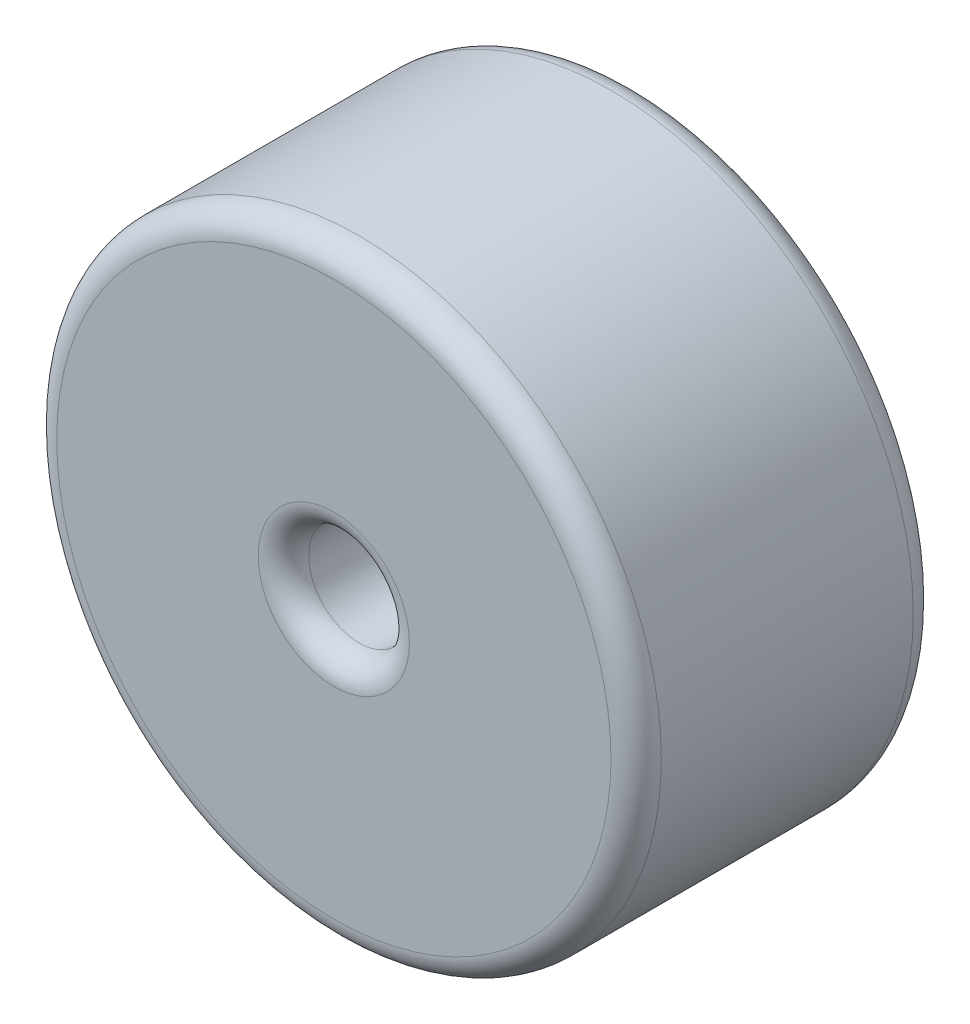
SolidWorks part; units mm, degrees
ref_plane "前视基准面" through (0, 0, 0) normal (0, 0, 1) x (1, 0, 0)
ref_plane "上视基准面" through (0, 0, 0) normal (0, 1, 0) x (1, 0, 0)
ref_plane "右视基准面" through (0, 0, 0) normal (1, 0, 0) x (0, 0, -1)
sketch "草图1" plane through (0, 0, 0) normal (0, 0, 1) x (1, 0, 0)
  circle A0 centre (0, 0) radius 12
  dimension "D1" = 24
extrude "凸台-拉伸1" add sketch "草图1" along normal blind 12
fillet "圆角1" radius 1 2 edges at (12, 0, 12) (12, 0, 0)
sketch "草图2" plane through (0, 0, 0) normal (0, 0, -1) x (-1, 0, 0)
  circle A0 centre (0, 0) radius 2
  dimension "D1" = 4
extrude "切除-拉伸1" cut sketch "草图2" against normal blind 12
fillet "圆角2" radius 1 2 edges at (-2, 0, 12) (-2, 0, 0)
